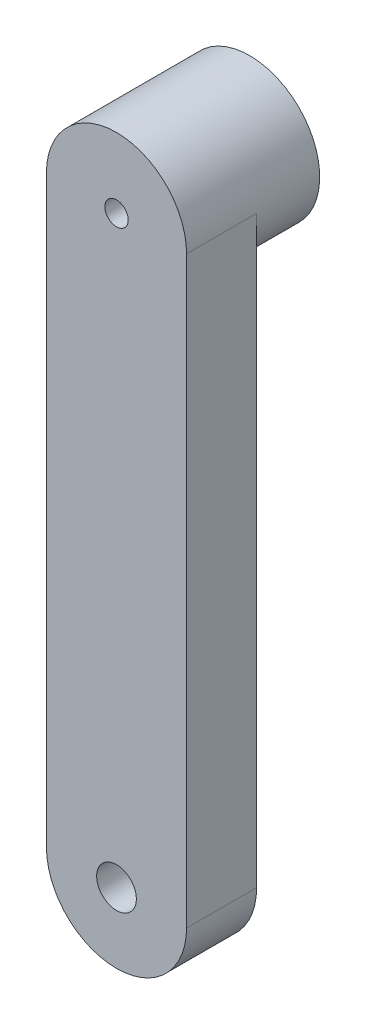
SolidWorks part; units mm, degrees
ref_plane "Plano frontal" through (0, 0, 0) normal (0, 0, 1) x (1, 0, 0)
ref_plane "Plano superior" through (0, 0, 0) normal (0, 1, 0) x (1, 0, 0)
ref_plane "Plano direito" through (0, 0, 0) normal (1, 0, 0) x (0, 0, -1)
sketch "Esboço1" plane through (0, 0, 0) normal (0, 0, 1) x (1, 0, 0)
  line L0 (0, 0) -> (0, 25) construction
  line L1 (-3, 0) -> (-3, 25)
  line L2 (3, 0) -> (3, 25)
  arc A0 (-3, 0) -> (3, 0) centre (0, 0) ccw
  arc A1 (3, 25) -> (-3, 25) centre (0, 25) ccw
  point P3 (0, 12.5)
  dimension "D1" = 25
  dimension "D2" = 6
extrude "Ressalto-extrusão1" add sketch "Esboço1" along normal blind 3
sketch "Esboço2" plane through (0, 0, 3) normal (0, 0, 1) x (1, 0, 0)
  circle A0 centre (0, 0) radius 0.85
  dimension "D1" = 1.7
extrude "Corte-extrusão1" cut sketch "Esboço2" against normal up to next
sketch "Esboço4" plane through (0, 0, 0) normal (0, 0, -1) x (-1, 0, 0)
  circle A0 centre (0, 25) radius 3
  arc A1 (3, 25) -> (-3, 25) centre (0, 25) ccw construction
extrude "Ressalto-extrusão2" add sketch "Esboço4" along normal blind 2.7
sketch "Esboço3" plane through (0, 0, 3) normal (0, 0, 1) x (1, 0, 0)
  circle A0 centre (0, 25) radius 0.5
  arc A1 (3, 25) -> (-3, 25) centre (0, 25) ccw construction
  dimension "D1" = 1
extrude "Corte-extrusão2" cut sketch "Esboço3" against normal up to next
